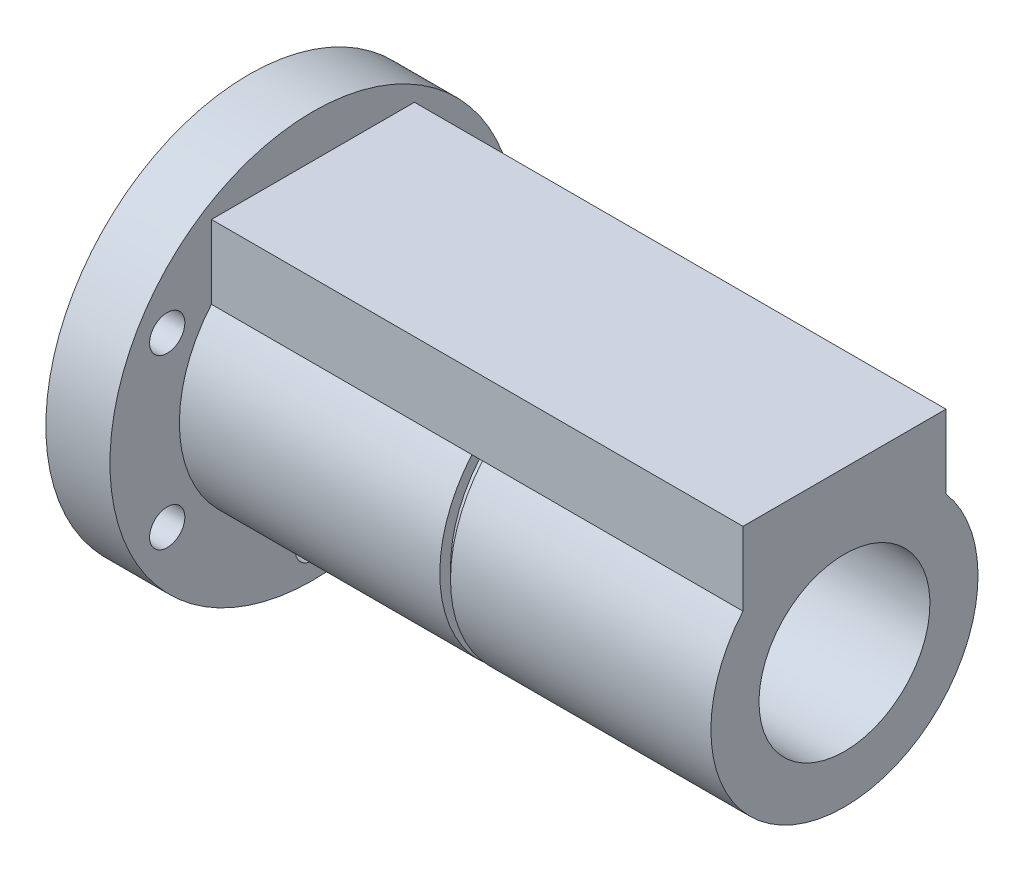
SolidWorks part; units mm, degrees
material "1.0037 (S235JR)"
ref_plane "Front Plane" through (0, 0, 0) normal (0, 0, 1) x (1, 0, 0)
ref_plane "Top Plane" through (0, 0, 0) normal (0, 1, 0) x (1, 0, 0)
ref_plane "Right Plane" through (0, 0, 0) normal (1, 0, 0) x (0, 0, -1)
sketch "Sketch1" plane through (0, 0, 0) normal (0, 0, 1) x (1, 0, 0)
  line L0 (-55.75, 38) -> (-43.75, 38)
  line L1 (-43.75, 38) -> (-43.75, 25)
  line L2 (-43.75, 25) -> (5, 25)
  line L3 (55.75, 25) -> (55.75, 16)
  line L4 (55.75, 16) -> (-55.75, 16)
  line L5 (-55.75, 16) -> (-55.75, 38)
  line L6 (5, 25) -> (5, 23)
  line L7 (5, 23) -> (7, 23)
  line L8 (7, 23) -> (7, 25)
  line L9 (7, 25) -> (55.75, 25)
  line L10 (-82.106, 0) -> (82.106, 0) construction
  point P12 (0, 16)
  dimension "D1" = 2
  dimension "D2" = 32
  dimension "D3" = 50
  dimension "D4" = 76
  dimension "D5" = 12
  dimension "L+1.5" = 111.5
  dimension "D7" = 99.5
  dimension "D8" = 48.75
  dimension "D9" = 48.75
revolve "Revolve1" add sketch "Sketch1" angle 360 about L10
sketch "Sketch2" plane through (-55.75, 0, 0) normal (-1, 0, 0) x (0, 0, 1)
  circle A0 centre (0, 0) radius 31.5 construction
  circle A1 centre (0, -31.5) radius 3.3
  dimension "D1" = 6.6
  dimension "D2" = 63
extrude "Cut-Extrude1" cut sketch "Sketch2" against normal up to next
sketch "Sketch3" plane through (-55.75, 0, 0) normal (-1, 0, 0) x (0, 0, 1)
  circle A0 centre (0, -31.5) radius 5.5
  dimension "D1" = 11
extrude "Cut-Extrude2" cut sketch "Sketch3" against normal blind 6
pattern_circular "CirPattern1" count 6 over 360 about axis through (0, 0, 0) along (1, 0, 0) skipping 3 of "Cut-Extrude1", "Cut-Extrude2"
sketch "Sketch5" plane through (55.75, 0, 0) normal (1, 0, 0) x (0, 0, -1)
  line L1 (-19, 30) -> (19, 30)
  line L2 (-19, 30) -> (-19, 16.2481)
  line L4 (19, 30) -> (19, 16.2481)
  line L5 (-19, 30) -> (0, 0) construction
  line L6 (0, 0) -> (19, 30) construction
  circle A0 centre (0, 0) radius 25 construction
  arc A1 (19, 16.2481) -> (-19, 16.2481) centre (0, 0) ccw
  point P0 (0, 0)
  dimension "D1" = 30
  dimension "D2" = 38
extrude "Boss-Extrude1" add sketch "Sketch5" against normal up to surface (99.5 mm away) up to face at (-43.75, -19.05, -27.2798)
